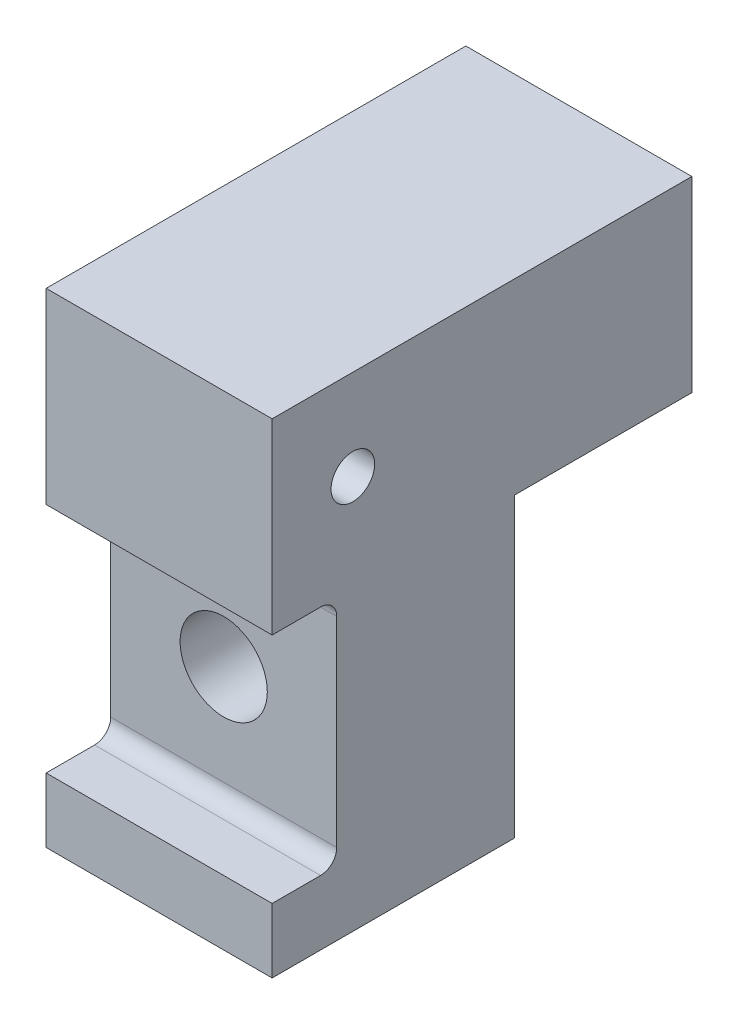
SolidWorks part; units mm, degrees
ref_plane "Front Plane" through (0, 0, 0) normal (0, 0, 1) x (1, 0, 0)
ref_plane "Top Plane" through (0, 0, 0) normal (0, 1, 0) x (1, 0, 0)
ref_plane "Right Plane" through (0, 0, 0) normal (1, 0, 0) x (0, 0, -1)
sketch "Sketch1" plane through (0, 0, 0) normal (0, 1, 0) x (1, 0, 0)
  line L1 (-3.5, -6.5) -> (3.5, -6.5)
  line L2 (-3.5, -6.5) -> (-3.5, 6.5)
  line L3 (-3.5, 6.5) -> (3.5, 6.5)
  line L4 (3.5, -6.5) -> (3.5, 6.5)
  line L5 (-3.5, -6.5) -> (3.5, 6.5) construction
  line L6 (-3.5, 6.5) -> (3.5, -6.5) construction
  point P0 (0, 0)
  dimension "D1" = 7
  dimension "D2" = 13
extrude "Boss-Extrude1" add sketch "Sketch1" along normal blind 15
sketch "Sketch9" plane through (-3.5, 0, 0) normal (-1, 0, 0) x (0, 0, 1)
  line L0 (4.5, 2) -> (6.5, 2)
  line L1 (4.5, 2) -> (4.5, 9.2)
  line L2 (6.5, 2) -> (6.5, 9.2)
  line L3 (4.5, 9.2) -> (6.5, 9.2)
  line L4 (4.5, 2) -> (6.5, 9.2) construction
  line L5 (6.5, 2) -> (4.5, 9.2) construction
  line L7 (-6.5, 0) -> (6.5, 0) construction
  line L8 (6.5, 15) -> (6.5, 0) construction
  point P1 (5.5, 5.6)
  dimension "D1" = 7.2
  dimension "D2" = 2
  dimension "D3" = 2
extrude "Cut-Extrude6" cut sketch "Sketch9" against normal through all
sketch "Sketch20" plane through (0, 0, 4.5) normal (0, 0, 1) x (1, 0, 0)
  line L0 (-3.5, 9.2) -> (3.5, 2) construction
  circle A0 centre (0, 5.6) radius 1.35
  dimension "D1" = 2.7
extrude "Cut-Extrude13" cut sketch "Sketch20" against normal through all
sketch "Sketch21" plane through (0, 0, -6.5) normal (0, 0, -1) x (-1, 0, 0)
  circle A0 centre (0, 5.6) radius 2.4
  dimension "D1" = 4.8
extrude "Cut-Extrude14" cut sketch "Sketch21" against normal offset from surface (8 mm away) 3 up to face at (1.35, 5.6, 4.5)
fillet "Fillet1" radius 0.5 2 edges at (0, 2, 4.5) (0, 9.2, 4.5)
ref_plane "Plane1" through (0, 12.2, 0) normal (0, -1, 0) x (-1, 0, 0)
sketch "Sketch16" plane through (0, 12.2, 0) normal (0, -1, 0) x (-1, 0, 0)
  line L0 (0, 6.5) -> (0, -2.5)
  line L1 (-3.5, 6.5) -> (3.5, 6.5) construction
  line L2 (-1.5, -4) -> (-3.5, -4)
  line L4 (-3.5, -6.5) -> (-3.5, 6.5) construction
  arc A0 (0, -2.5) -> (-1.5, -4) centre (-1.5, -2.5) cw
  dimension "D1" = 1.5
  dimension "D2" = 9
sketch "Sketch17" plane through (0, 0, -6.5) normal (0, 0, -1) x (-1, 0, 0)
  circle A0 centre (0, 12.2) radius 0.675
  dimension "D1" = 1.35
sweep "Cut-Sweep1" cut profiles "Sketch17" path "Sketch16"
sketch "Sketch19" plane through (-3.5, 0, 0) normal (-1, 0, 0) x (0, 0, 1)
  line L0 (4, 12.2) -> (0.5, 12.2) construction
  line L1 (0.5, 12.2) -> (-3.5, 12.2) construction
  circle A0 centre (0.5, 12.2) radius 0.9
  circle A1 centre (-3.5, 12.2) radius 0.9
  circle A2 centre (4, 12.2) radius 0.675 construction
  point P4 (2.9468, 12.2545)
  dimension "D1" = 1.8
  dimension "D3" = 4
  dimension "D4" = 3.5
  dimension "D2" = 2
extrude "Cut-Extrude12" cut sketch "Sketch19" against normal blind 4
sketch "Sketch22" plane through (3.5, 0, 0) normal (1, 0, 0) x (0, 0, -1)
  line L0 (-6.5, 9.2) -> (-5, 9.2) construction
  line L1 (6.5, 0) -> (1, 0)
  line L2 (6.5, 0) -> (6.5, 9.2)
  line L3 (6.5, 9.2) -> (1, 9.2)
  line L4 (1, 0) -> (1, 9.2)
  line L5 (-4.5, 8.7) -> (-4.5, 2.5) construction
  dimension "D1" = 5.5
extrude "Cut-Extrude15" cut sketch "Sketch22" against normal through all
